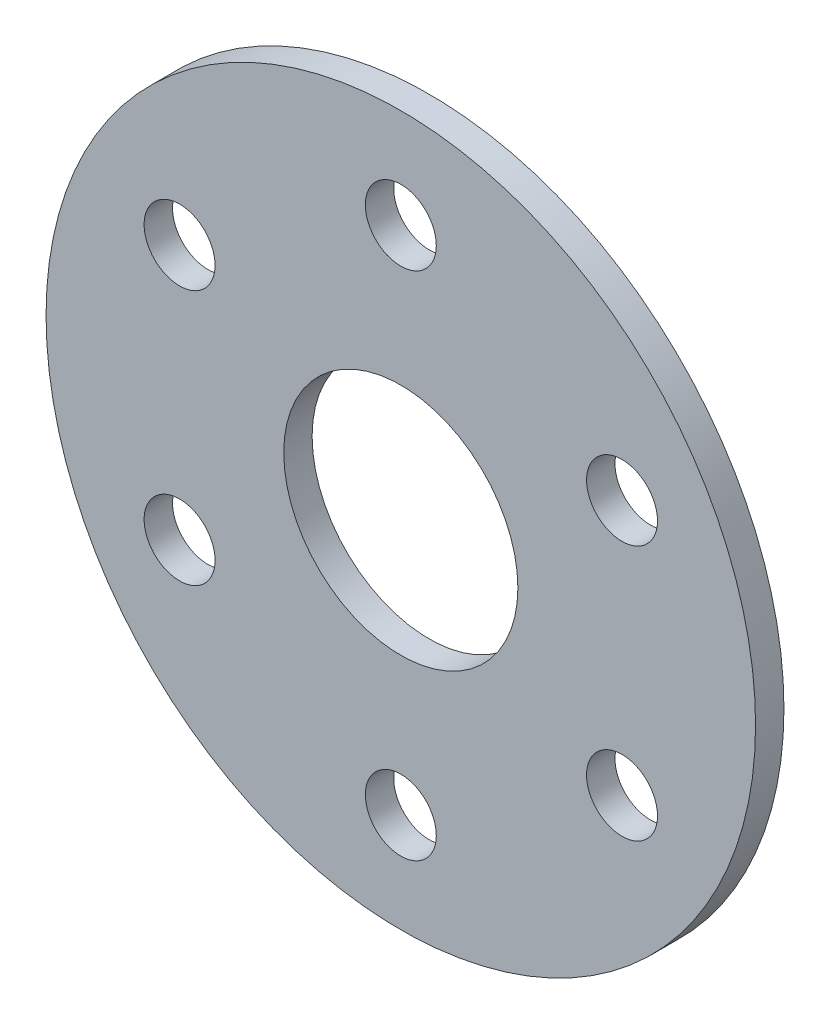
SolidWorks part; units mm, degrees
ref_plane "Front Plane" through (0, 0, 0) normal (0, 0, 1) x (1, 0, 0)
ref_plane "Top Plane" through (0, 0, 0) normal (0, 1, 0) x (1, 0, 0)
ref_plane "Right Plane" through (0, 0, 0) normal (1, 0, 0) x (0, 0, -1)
sketch "Sketch1"
  circle A0 centre (0, 0) radius 8.25
  circle A1 centre (0, 0) radius 25
  circle A2 centre (0, 0) radius 18 construction
  circle A3 centre (0, 18) radius 2.5
  circle A4 centre (15.5885, 9) radius 2.5
  circle A5 centre (15.5885, -9) radius 2.5
  circle A6 centre (0, -18) radius 2.5
  circle A7 centre (-15.5885, -9) radius 2.5
  circle A8 centre (-15.5885, 9) radius 2.5
  point P19 (0, 0)
other "AlignGroup1" parameters "D1"=163.5858, "D2"=32.895, "D3"=11.7094, "D4"=8.4918, "D6"=0, "D7"=0, "D5"=6
other "AlignGroup2"
extrude "Boss-Extrude1" add sketch "Sketch1" along normal mid plane 2
